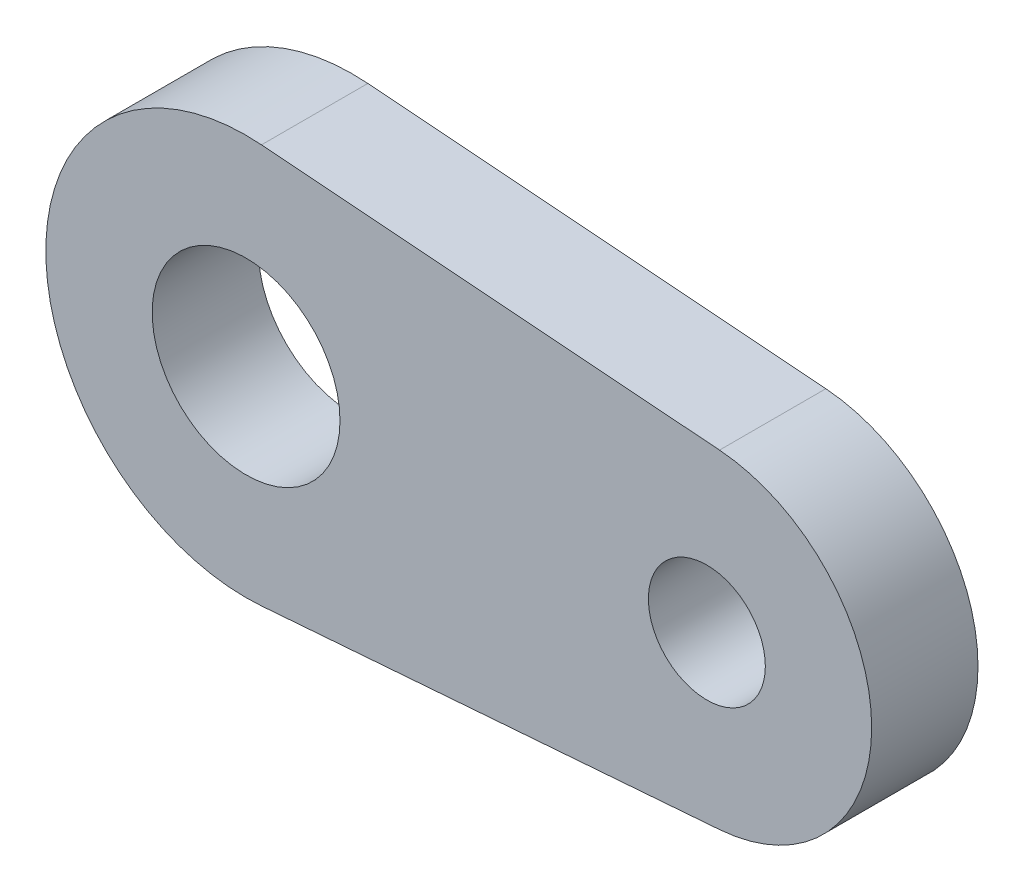
SolidWorks part; units mm, degrees
ref_plane "Front Plane" through (0, 0, 0) normal (0, 0, 1) x (1, 0, 0)
ref_plane "Top Plane" through (0, 0, 0) normal (0, 1, 0) x (1, 0, 0)
ref_plane "Right Plane" through (0, 0, 0) normal (1, 0, 0) x (0, 0, -1)
sketch "Sketch1" plane through (0, 0, 0) normal (0, 0, 1) x (1, 0, 0)
  line L0 (0.4346, 5.6333) -> (13.3577, 4.6362)
  line L1 (13.3577, -4.6362) -> (0.4346, -5.6333)
  line L2 (-2.65, 0) -> (-5.65, 0) construction
  line L3 (14.65, 0) -> (17.65, 0) construction
  circle A0 centre (0, 0) radius 2.65
  circle A1 centre (13, 0) radius 1.65
  arc A2 (0.4346, -5.6333) -> (0.4346, 5.6333) centre (0, 0) cw
  arc A3 (13.3577, 4.6362) -> (13.3577, -4.6362) centre (13, 0) cw
  circle A4 centre (0, 0) radius 8 construction
  circle A5 centre (13, 0) radius 3 construction
  point P10 (8, 0)
  point P12 (10, 0)
  point P17 (15.5015, 0)
  point P18 (17.2435, 1.2086)
  point P19 (0, 0)
  dimension "D1" = 5.3
  dimension "D2" = 3.3
  dimension "D3" = 16
  dimension "D4" = 6
  dimension "D6" = 3
  dimension "D5" = 2
extrude "Boss-Extrude1" add sketch "Sketch1" along normal mid plane 3
